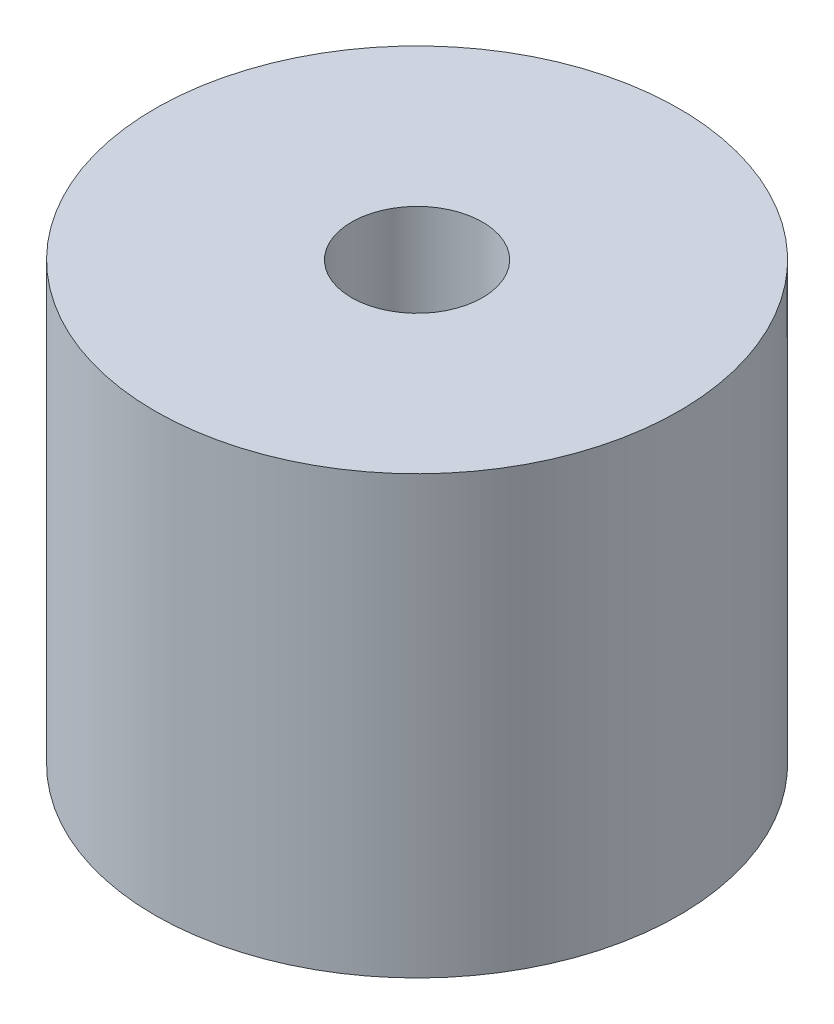
SolidWorks part; units mm, degrees
ref_plane "Front Plane" through (0, 0, 0) normal (0, 0, 1) x (1, 0, 0)
ref_plane "Top Plane" through (0, 0, 0) normal (0, 1, 0) x (1, 0, 0)
ref_plane "Right Plane" through (0, 0, 0) normal (1, 0, 0) x (0, 0, -1)
sketch "Sketch1" plane through (0, 0, 0) normal (0, 1, 0) x (1, 0, 0)
  circle A0 centre (0, 0) radius 12
extrude "Boss-Extrude1" add sketch "Sketch1" along normal blind 20 contours A0
sketch "Sketch2" plane through (0, 0, 0) normal (0, -1, 0) x (1, 0, 0)
  line L1 (3.05, 2.74) -> (3.05, -2.74)
  arc A0 (3.05, 2.74) -> (3.05, -2.74) centre (0, 0) ccw
extrude "Cut-Extrude1" cut sketch "Sketch2" against normal blind 13 contours A0 L1
sketch "Sketch3" plane through (0, 20, 0) normal (0, 1, 0) x (1, 0, 0)
  circle A0 centre (0, 0) radius 3
extrude "Cut-Extrude2" cut sketch "Sketch3" against normal blind 13
